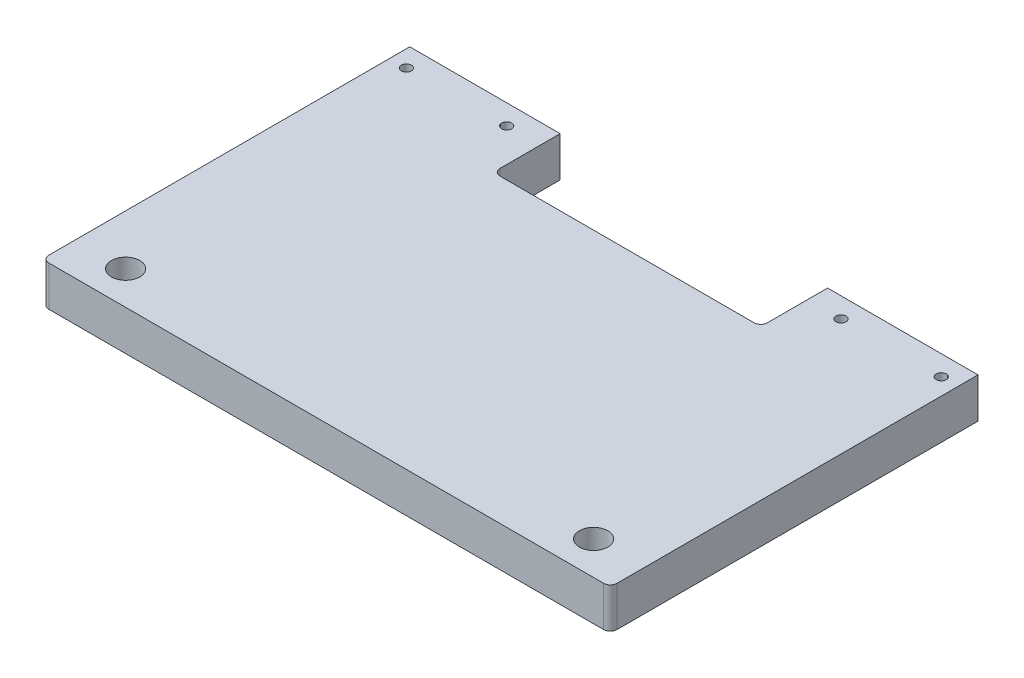
SolidWorks part; units mm, degrees
ref_plane "Front Plane" through (0, 0, 0) normal (0, 0, 1) x (1, 0, 0)
ref_plane "Top Plane" through (0, 0, 0) normal (0, 1, 0) x (1, 0, 0)
ref_plane "Right Plane" through (0, 0, 0) normal (1, 0, 0) x (0, 0, -1)
sketch "Sketch1" plane through (0, 0, 0) normal (0, 1, 0) x (1, 0, 0)
  line L0 (85, 110) -> (85, 0) construction
  line L1 (0, 0) -> (170, 0)
  line L2 (0, 0) -> (0, 110)
  line L3 (0, 110) -> (45, 110)
  line L4 (170, 0) -> (170, 110)
  line L5 (0, 104) -> (170, 104) construction
  line L6 (45, 110) -> (45, 90)
  line L7 (45, 90) -> (125, 90)
  line L8 (125, 90) -> (125, 110)
  line L9 (125, 110) -> (170, 110)
  circle A0 centre (155, 10) radius 4.25
  circle A1 centre (15, 10) radius 4.25
  circle A2 centre (5, 104) radius 1.5
  circle A3 centre (35, 104) radius 1.5
  circle A4 centre (165, 104) radius 1.5
  circle A5 centre (135, 104) radius 1.5
  point P25 (85, 90)
  dimension "D3" = 8.5
  dimension "D7" = 3
  dimension "D1" = 170
  dimension "D2" = 110
  dimension "D4" = 15
  dimension "D5" = 10
  dimension "D6" = 6
  dimension "D8" = 5
  dimension "D9" = 30
  dimension "D10" = 45
  dimension "D11" = 20
extrude "Boss-Extrude1" add sketch "Sketch1" along normal blind 12
fillet "Fillet1" radius 2 4 edges at (170, 6, 0) (0, 6, 0) (125, 6, -90) (45, 6, -90)
